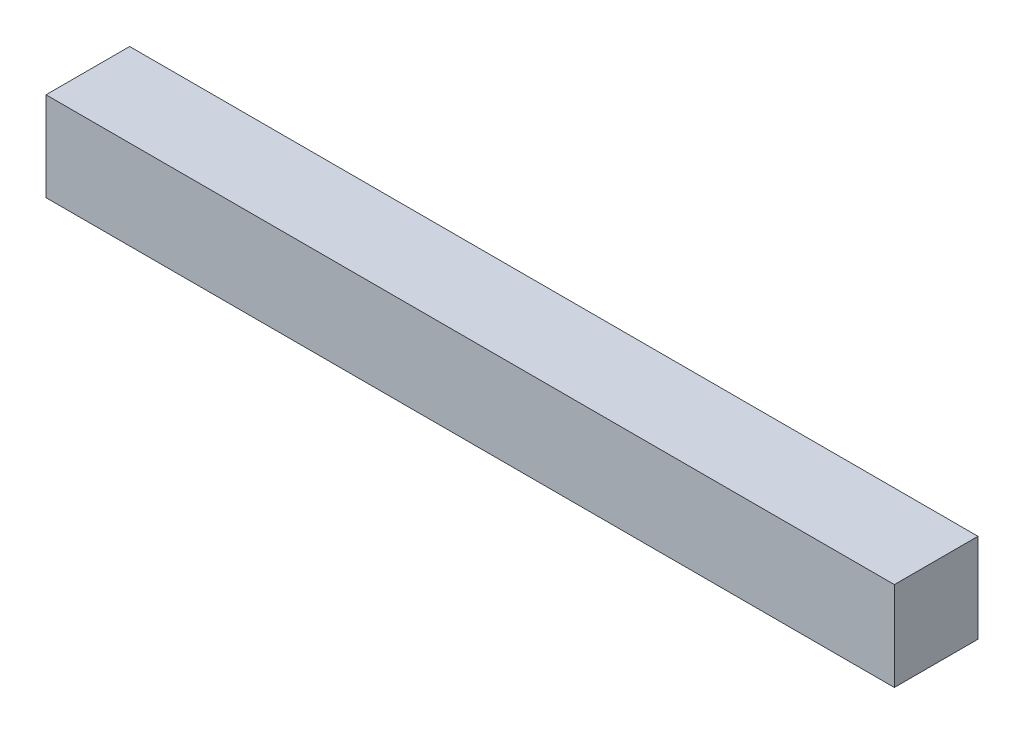
SolidWorks part; units mm, degrees
ref_plane "Front Plane" through (0, 0, 0) normal (0, 0, 1) x (1, 0, 0)
ref_plane "Top Plane" through (0, 0, 0) normal (0, 1, 0) x (1, 0, 0)
ref_plane "Right Plane" through (0, 0, 0) normal (1, 0, 0) x (0, 0, -1)
sketch "Croquis1" plane through (0, 0, 0) normal (0, 1, 0) x (1, 0, 0)
  line L1 (-25.36, 2.5) -> (25.36, 2.5)
  line L2 (-25.36, 2.5) -> (-25.36, -2.5)
  line L3 (-25.36, -2.5) -> (25.36, -2.5)
  line L4 (25.36, 2.5) -> (25.36, -2.5)
  line L5 (-25.36, 2.5) -> (25.36, -2.5) construction
  line L6 (-25.36, -2.5) -> (25.36, 2.5) construction
  point P0 (0, 0)
  dimension "D1" = 50.72
  dimension "D2" = 5
extrude "Saliente-Extruir1" add sketch "Croquis1" along normal blind 5.33
